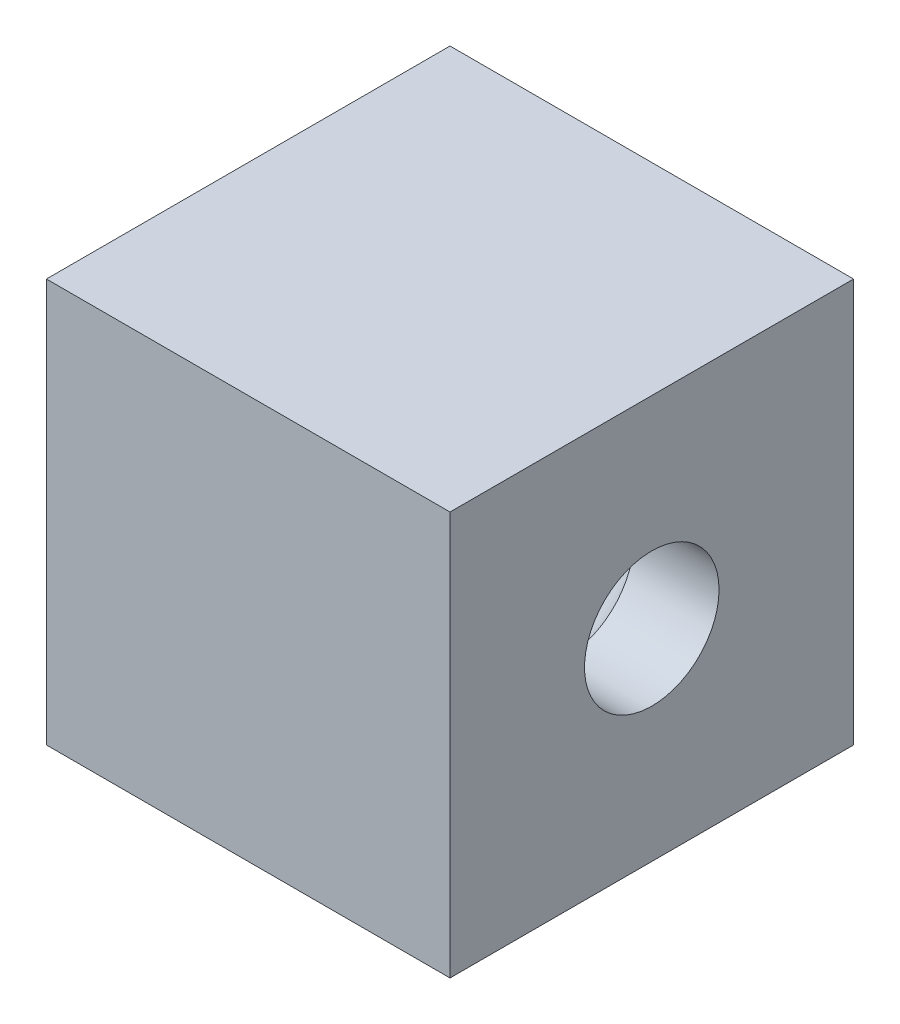
SolidWorks part; units mm, degrees
ref_plane "Front Plane" through (0, 0, 0) normal (0, 0, 1) x (1, 0, 0)
ref_plane "Top Plane" through (0, 0, 0) normal (0, 1, 0) x (1, 0, 0)
ref_plane "Right Plane" through (0, 0, 0) normal (1, 0, 0) x (0, 0, -1)
sketch "Sketch1" plane through (0, 0, 0) normal (0, 1, 0) x (1, 0, 0)
  line L1 (0, 0) -> (30, 0)
  line L2 (0, 0) -> (0, 30)
  line L3 (0, 30) -> (30, 30)
  line L4 (30, 0) -> (30, 30)
  dimension "D1" = 30
  dimension "D2" = 30
extrude "Boss-Extrude1" add sketch "Sketch1" along normal blind 30 contours L2 L1 L4 L3
sketch "Sketch2" plane through (30, 0, 0) normal (1, 0, 0) x (0, 0, -1)
  line L1 (30, 30) -> (30, 0) construction
  line L3 (0, 0) -> (30, 0) construction
  circle A0 centre (15, 15) radius 5
  point P2 (15.8895, 15.2828)
  point P6 (0, 0)
  point P10 (15, 0)
  dimension "D1" = 10
  dimension "D2" = 15
  dimension "D3" = 15
extrude "Cut-Extrude1" cut sketch "Sketch2" against normal blind 15
ref_plane "Plane1" through (15, 0, 0) normal (1, 0, 0) x (0, 0, -1)
sketch "Sketch4" plane through (15, 0, 0) normal (1, 0, 0) x (0, 0, -1)
  line L0 (25, 15) -> (5, 15)
  arc A0 (5, 15) -> (25, 15) centre (15, 15) ccw
  circle A1 centre (15, 15) radius 5 construction
  dimension "D1" = 20
revolve "Cut-Revolve1" cut sketch "Sketch4" angle 360 about L0
